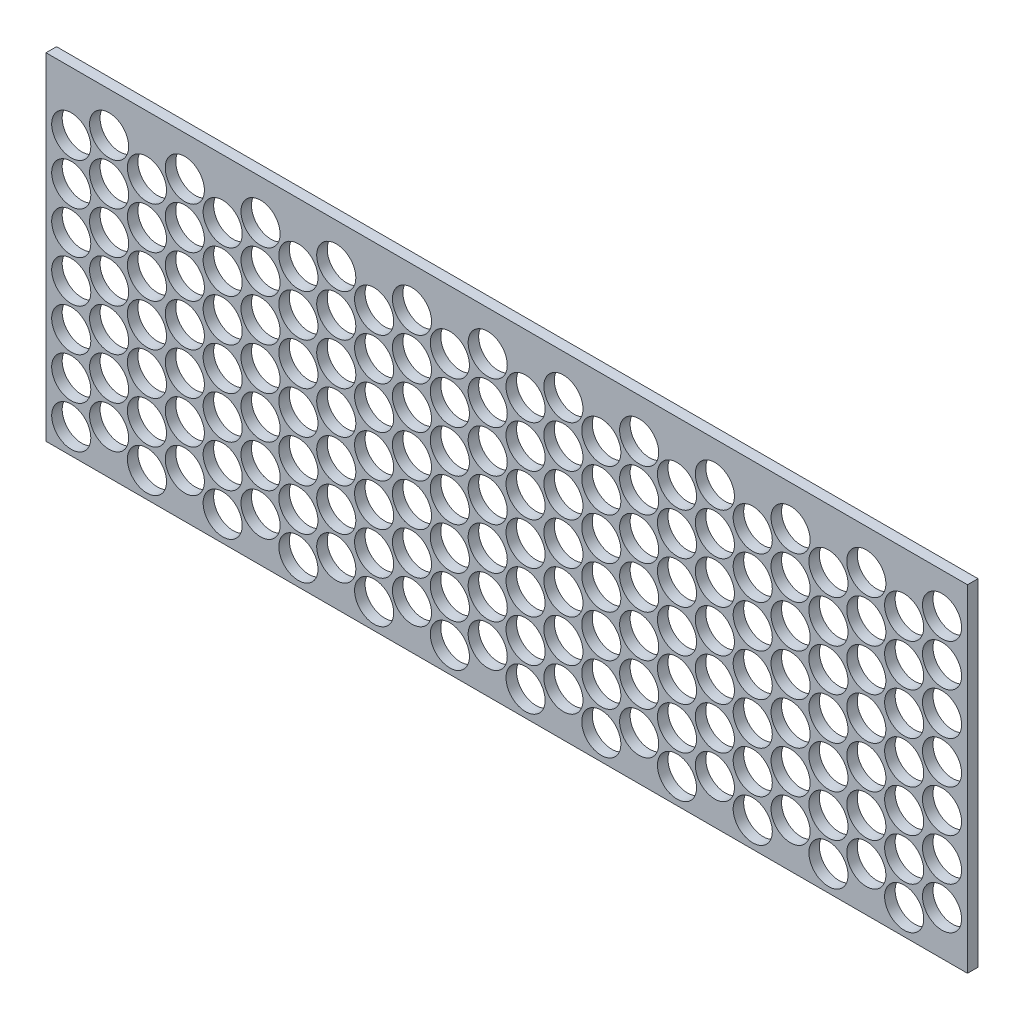
SolidWorks part; units mm, degrees
ref_plane "Front Plane" through (0, 0, 0) normal (0, 0, 1) x (1, 0, 0)
ref_plane "Top Plane" through (0, 0, 0) normal (0, 1, 0) x (1, 0, 0)
ref_plane "Right Plane" through (0, 0, 0) normal (1, 0, 0) x (0, 0, -1)
sketch "Sketch1" plane through (0, 0, 0) normal (0, 0, 1) x (1, 0, 0)
  line L1 (0, 0) -> (438.1, 0)
  line L2 (0, 0) -> (0, 160)
  line L3 (0, 160) -> (438.1, 160)
  line L4 (438.1, 0) -> (438.1, 160)
  dimension "D1" = 160
  dimension "D2" = 438.1
extrude "Boss-Extrude1" add sketch "Sketch1" along normal blind 5 contours L2 L3 L4 L1
sketch "Sketch2" plane through (0, 0, 5) normal (0, 0, 1) x (1, 0, 0)
  line L0 (0, 0) -> (0, 160) construction
  line L1 (0, 0) -> (438.1, 0) construction
  circle A0 centre (12, 12) radius 9.3
  circle A1 centre (30, 21) radius 9.3
  point P8 (0, 0)
  point P11 (35.5548, 20.0148)
  dimension "D1" = 12
  dimension "D3" = 18.6
  dimension "D2" = 12
  dimension "D4" = 18
  dimension "D5" = 9
extrude "Cut-Extrude1" cut sketch "Sketch2" against normal up to surface (5 mm away) up to face at (219.05, 80, 0)
pattern_linear "LPattern1" count 12 spacing 36 along (1, 0, 0) count 7 spacing 20 along (0, 1, 0) of "Cut-Extrude1"
